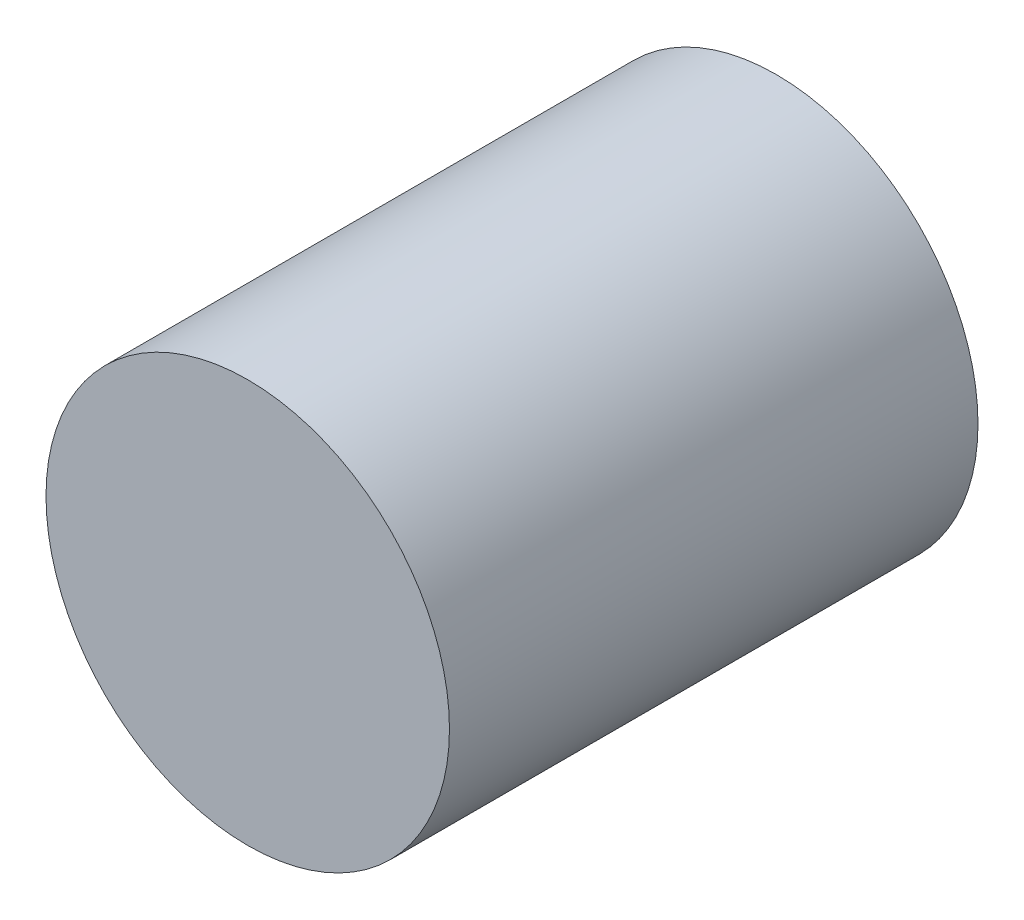
SolidWorks part; units mm, degrees
ref_plane "前视基准面" through (0, 0, 0) normal (0, 0, 1) x (1, 0, 0)
ref_plane "上视基准面" through (0, 0, 0) normal (0, 1, 0) x (1, 0, 0)
ref_plane "右视基准面" through (0, 0, 0) normal (1, 0, 0) x (0, 0, -1)
sketch "草图1" plane through (0, 0, 0) normal (0, 0, 1) x (1, 0, 0)
  circle A0 centre (0, 0) radius 8
  circle A1 centre (0, 0) radius 10
  dimension "D1" = 16
  dimension "D2" = 2
extrude "凸台-拉伸1" add sketch "草图1" along normal blind 24.2
sketch "草图2" plane through (0, 0, 24.2) normal (0, 0, 1) x (1, 0, 0)
  circle A0 centre (0, 0) radius 10
extrude "凸台-拉伸2" add sketch "草图2" along normal blind 2
sketch "草图3" plane through (0, 0, 24.2) normal (0, 0, -1) x (-1, 0, 0)
  circle A0 centre (0, 0) radius 3
extrude "凸台-拉伸3" add sketch "草图3" along normal up to surface (24.2 mm away) up to face at (10, 0, 0)
